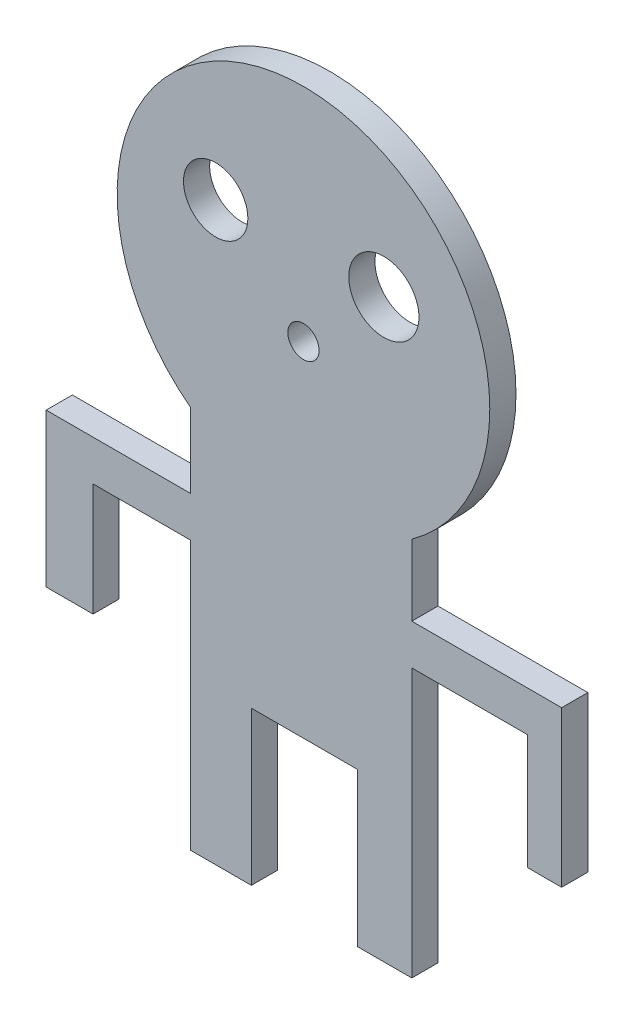
SolidWorks part; units mm, degrees
ref_plane "Front Plane" through (0, 0, 0) normal (0, 0, 1) x (1, 0, 0)
ref_plane "Top Plane" through (0, 0, 0) normal (0, 1, 0) x (1, 0, 0)
ref_plane "Right Plane" through (0, 0, 0) normal (1, 0, 0) x (0, 0, -1)
sketch "Sketch1" plane through (0, 0, 0) normal (0, 0, 1) x (1, 0, 0)
  line L0 (-43.1667, -100.459) -> (-43.1667, -144.3864)
  line L6 (-43.1667, -56.5317) -> (-43.1667, -85.0113)
  line L7 (-19.8961, -144.3864) -> (20.7153, -144.3864)
  line L8 (41.35, -57.8738) -> (41.35, -85.0113)
  line L10 (-43.1667, -144.3864) -> (-43.1667, -202.9776)
  line L11 (-43.1667, -202.9776) -> (-19.8961, -202.9776)
  line L12 (-19.8961, -144.3864) -> (-19.8961, -202.9776)
  line L14 (41.35, -144.3864) -> (41.35, -202.9776)
  line L15 (41.35, -202.9776) -> (20.7153, -202.9776)
  line L16 (20.7153, -144.3864) -> (20.7153, -202.9776)
  line L17 (41.35, -85.0113) -> (98.5537, -85.0113)
  line L19 (41.35, -100.459) -> (85.5, -100.459)
  line L20 (98.5537, -85.0113) -> (98.5537, -100.459)
  line L21 (-43.1667, -85.0113) -> (-98.218, -85.0113)
  line L23 (-43.1667, -100.459) -> (-80.3296, -100.459)
  line L24 (-98.218, -85.0113) -> (-98.218, -100.459)
  line L26 (-98.218, -100.459) -> (-98.218, -143.511)
  line L27 (-98.218, -143.511) -> (-80.3296, -143.511)
  line L28 (-80.3296, -100.459) -> (-80.3296, -143.511)
  line L30 (98.5537, -100.459) -> (98.5537, -144.3864)
  line L31 (98.5537, -144.3864) -> (85.5, -144.3864)
  line L32 (85.5, -100.459) -> (85.5, -144.3864)
  line L33 (41.35, -100.459) -> (41.35, -144.3864)
  arc A0 (41.35, -57.8738) -> (-43.1667, -56.5317) centre (0, 0) ccw
  circle A1 centre (-33.5174, 16.8514) radius 12.288
  circle A2 centre (30.6885, 16.8514) radius 13.4023
  circle A3 centre (0, -13.2378) radius 5.9667
  arc A4 (41.35, -34.0869) -> (-41.0989, -34.0869) centre (0.1255, 7.1376) cw construction
  arc A5 (-47.4425, -40.4304) -> (47.6935, -40.4304) centre (0.1255, 7.1376) ccw construction
  arc A6 (-34.7554, -27.7434) -> (35.0065, -27.7434) centre (0.1255, 7.1376) ccw construction
  arc A7 (-34.7554, -27.7434) -> (-47.4425, -40.4304) centre (-41.0989, -34.0869) ccw construction
  arc A8 (47.6935, -40.4304) -> (35.0065, -27.7434) centre (41.35, -34.0869) ccw construction
  point P13 (0.1255, -51.1626)
extrude "Boss-Extrude1" add sketch "Sketch1" along normal blind 10
